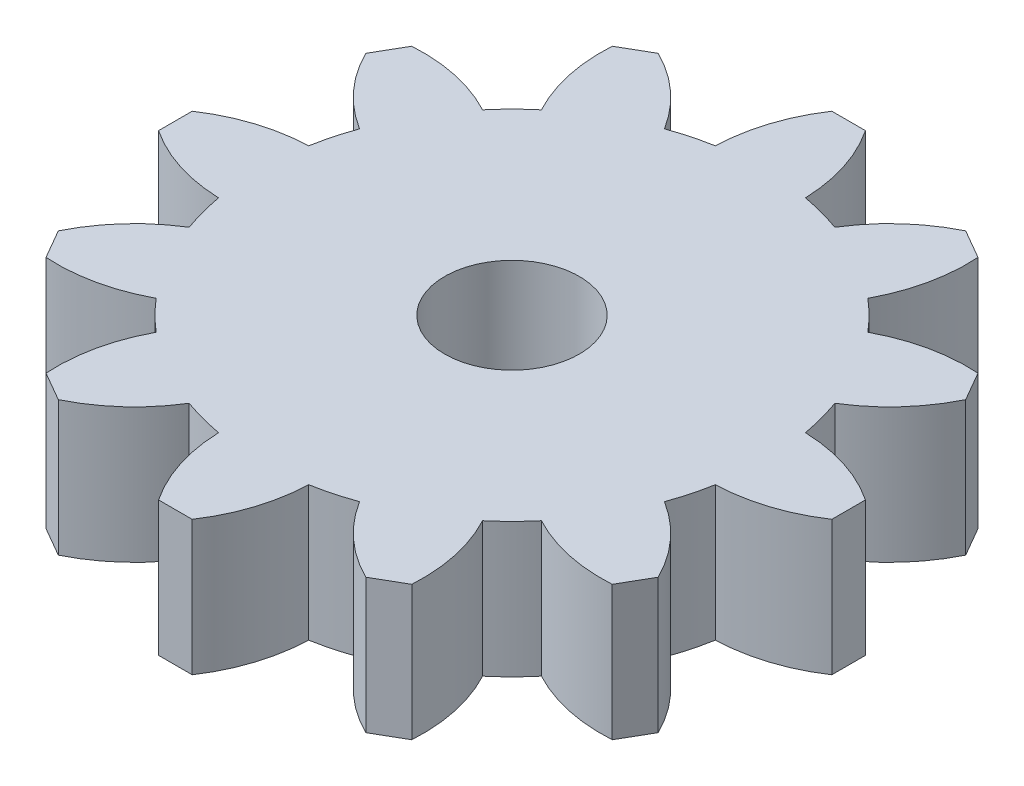
SolidWorks part; units mm, degrees
ref_plane "Front Plane" through (0, 0, 0) normal (0, 0, 1) x (1, 0, 0)
ref_plane "Top Plane" through (0, 0, 0) normal (0, 1, 0) x (1, 0, 0)
ref_plane "Right Plane" through (0, 0, 0) normal (1, 0, 0) x (0, 0, -1)
sketch "Sketch1" plane through (0, 0, 0) normal (0, 1, 0) x (1, 0, 0)
  line L0 (0, 4) -> (0, 21.8422) construction
  line L1 (-1, 20) -> (1, 20)
  line L2 (9.134, 17.8205) -> (10.866, 16.8205)
  line L3 (16.8205, 10.866) -> (17.8205, 9.134)
  line L4 (20, 1) -> (20, -1)
  line L5 (17.8205, -9.134) -> (16.8205, -10.866)
  line L6 (10.866, -16.8205) -> (9.134, -17.8205)
  line L7 (1, -20) -> (-1, -20)
  line L8 (-9.134, -17.8205) -> (-10.866, -16.8205)
  line L9 (-16.8205, -10.866) -> (-17.8205, -9.134)
  line L10 (-20, -1) -> (-20, 1)
  line L11 (-17.8205, 9.134) -> (-16.8205, 10.866)
  line L12 (-10.866, 16.8205) -> (-9.134, 17.8205)
  arc A0 (-2.675, 14.7596) -> (-5.0632, 14.1196) centre (0, 0) ccw
  circle A1 centre (0, 0) radius 4
  arc A2 (-1, 20) -> (-2.675, 14.7596) centre (7.3203, 14.4527) ccw
  arc A3 (1, 20) -> (2.675, 14.7596) centre (-7.3203, 14.4527) cw
  arc A4 (9.134, 17.8205) -> (5.0632, 14.1196) centre (13.5659, 8.8562) ccw
  arc A5 (10.866, 16.8205) -> (9.6964, 11.4446) centre (0.8868, 16.1765) cw
  arc A6 (16.8205, 10.866) -> (11.4446, 9.6964) centre (16.1765, 0.8868) ccw
  arc A7 (17.8205, 9.134) -> (14.1196, 5.0632) centre (8.8562, 13.5659) cw
  arc A8 (20, 1) -> (14.7596, 2.675) centre (14.4527, -7.3203) ccw
  arc A9 (20, -1) -> (14.7596, -2.675) centre (14.4527, 7.3203) cw
  arc A10 (17.8205, -9.134) -> (14.1196, -5.0632) centre (8.8562, -13.5659) ccw
  arc A11 (16.8205, -10.866) -> (11.4446, -9.6964) centre (16.1765, -0.8868) cw
  arc A12 (10.866, -16.8205) -> (9.6964, -11.4446) centre (0.8868, -16.1765) ccw
  arc A13 (9.134, -17.8205) -> (5.0632, -14.1196) centre (13.5659, -8.8562) cw
  arc A14 (1, -20) -> (2.675, -14.7596) centre (-7.3203, -14.4527) ccw
  arc A15 (-1, -20) -> (-2.675, -14.7596) centre (7.3203, -14.4527) cw
  arc A16 (-9.134, -17.8205) -> (-5.0632, -14.1196) centre (-13.5659, -8.8562) ccw
  arc A17 (-10.866, -16.8205) -> (-9.6964, -11.4446) centre (-0.8868, -16.1765) cw
  arc A18 (-16.8205, -10.866) -> (-11.4446, -9.6964) centre (-16.1765, -0.8868) ccw
  arc A19 (-17.8205, -9.134) -> (-14.1196, -5.0632) centre (-8.8562, -13.5659) cw
  arc A20 (-20, -1) -> (-14.7596, -2.675) centre (-14.4527, 7.3203) ccw
  arc A21 (-20, 1) -> (-14.7596, 2.675) centre (-14.4527, -7.3203) cw
  arc A22 (-17.8205, 9.134) -> (-14.1196, 5.0632) centre (-8.8562, 13.5659) ccw
  arc A23 (-16.8205, 10.866) -> (-11.4446, 9.6964) centre (-16.1765, 0.8868) cw
  arc A24 (-10.866, 16.8205) -> (-9.6964, 11.4446) centre (-0.8868, 16.1765) ccw
  arc A25 (-9.134, 17.8205) -> (-5.0632, 14.1196) centre (-13.5659, 8.8562) cw
  arc A26 (14.1196, -5.0632) -> (14.7596, -2.675) centre (0, 0) ccw
  arc A27 (14.7596, 2.675) -> (14.1196, 5.0632) centre (0, 0) ccw
  arc A28 (11.4446, 9.6964) -> (9.6964, 11.4446) centre (0, 0) ccw
  arc A29 (5.0632, 14.1196) -> (2.675, 14.7596) centre (0, 0) ccw
  arc A30 (-9.6964, 11.4446) -> (-11.4446, 9.6964) centre (0, 0) ccw
  arc A31 (-14.1196, 5.0632) -> (-14.7596, 2.675) centre (0, 0) ccw
  arc A32 (-14.7596, -2.675) -> (-14.1196, -5.0632) centre (0, 0) ccw
  arc A33 (-11.4446, -9.6964) -> (-9.6964, -11.4446) centre (0, 0) ccw
  arc A34 (-5.0632, -14.1196) -> (-2.675, -14.7596) centre (0, 0) ccw
  arc A35 (2.675, -14.7596) -> (5.0632, -14.1196) centre (0, 0) ccw
  arc A36 (9.6964, -11.4446) -> (11.4446, -9.6964) centre (0, 0) ccw
  point P80 (0, 0)
  dimension "D1" = 30
  dimension "D2" = 8
  dimension "D6" = 10
  dimension "D8" = 12
  dimension "D3" = 2
  dimension "D4" = 20
  dimension "D5" = 2
  dimension "D7" = 5.35
extrude "Boss-Extrude1" add sketch "Sketch1" along normal blind 8
